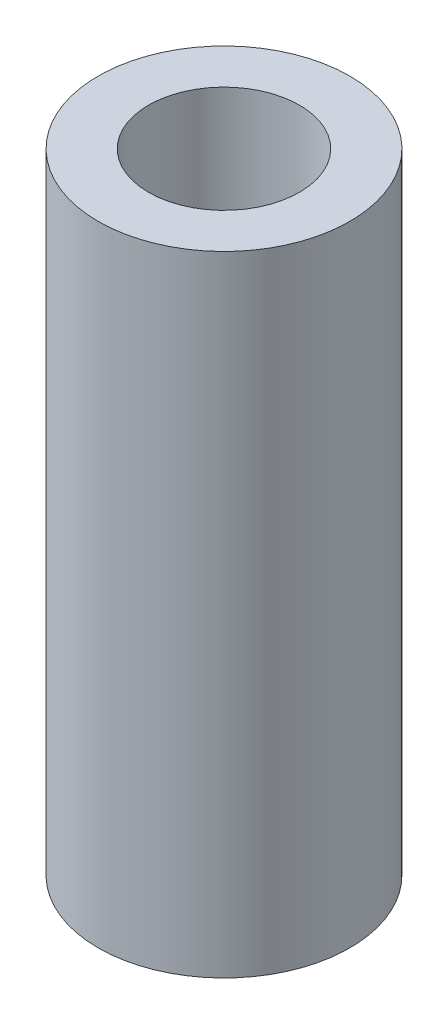
SolidWorks part; units mm, degrees
ref_plane "Front Plane" through (0, 0, 0) normal (0, 0, 1) x (1, 0, 0)
ref_plane "Top Plane" through (0, 0, 0) normal (0, 1, 0) x (1, 0, 0)
ref_plane "Right Plane" through (0, 0, 0) normal (1, 0, 0) x (0, 0, -1)
sketch "Sketch1" plane through (0, 0, 0) normal (0, 1, 0) x (1, 0, 0)
  circle A0 centre (0, 0) radius 10
  circle A1 centre (0, 0) radius 6
  dimension "D1" = 20
  dimension "D2" = 12
extrude "Boss-Extrude1" add sketch "Sketch1" along normal mid plane 50
scale "Scale1" scale about centroid uniform scaling yes scale factor 0.245
